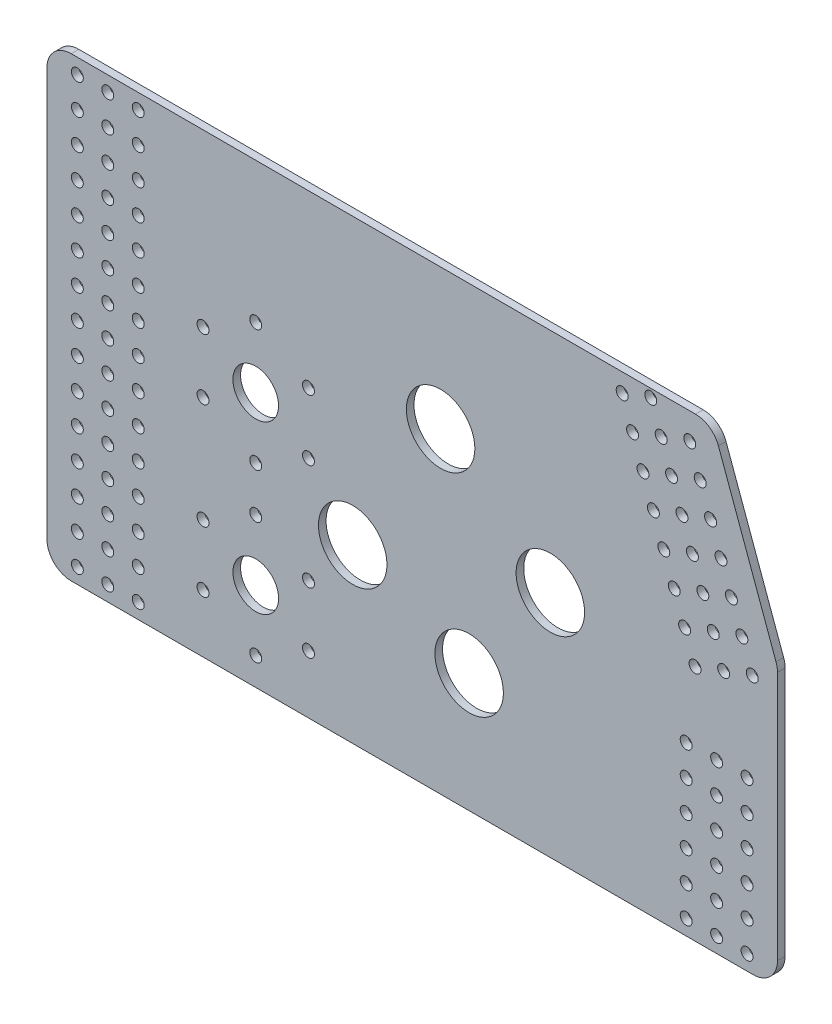
SolidWorks part; units mm, degrees
ref_plane "Front Plane" through (0, 0, 0) normal (0, 0, 1) x (1, 0, 0)
ref_plane "Top Plane" through (0, 0, 0) normal (0, 1, 0) x (1, 0, 0)
ref_plane "Right Plane" through (0, 0, 0) normal (1, 0, 0) x (0, 0, -1)
sketch "Sketch1" plane through (0, 0, 0) normal (0, 0, 1) x (1, 0, 0)
  line B0 (-152.4, 0) -> (152.4, 0)
  line B1 (152.4, 0) -> (152.4, 116.0843)
  line B2 (152.4, 116.0843) -> (125.3149, 190.5)
  line B3 (125.3149, 190.5) -> (-152.4, 190.5)
  line B4 (-152.4, 190.5) -> (-152.4, 0)
  circle B5 centre (-139.7, 184.15) radius 2.4892
  circle B6 centre (-127, 184.15) radius 2.4892
  circle B7 centre (-114.3, 184.15) radius 2.4892
  circle B8 centre (-127, 171.45) radius 2.4892
  circle B9 centre (-114.3, 171.45) radius 2.4892
  circle B10 centre (-127, 158.75) radius 2.4892
  circle B11 centre (-114.3, 158.75) radius 2.4892
  circle B12 centre (-127, 146.05) radius 2.4892
  circle B13 centre (-114.3, 146.05) radius 2.4892
  circle B14 centre (-127, 133.35) radius 2.4892
  circle B15 centre (-114.3, 133.35) radius 2.4892
  circle B16 centre (-127, 120.65) radius 2.4892
  circle B17 centre (-114.3, 120.65) radius 2.4892
  circle B18 centre (-127, 107.95) radius 2.4892
  circle B19 centre (-114.3, 107.95) radius 2.4892
  circle B20 centre (-127, 95.25) radius 2.4892
  circle B21 centre (-114.3, 95.25) radius 2.4892
  circle B22 centre (-127, 82.55) radius 2.4892
  circle B23 centre (-114.3, 82.55) radius 2.4892
  circle B24 centre (-127, 69.85) radius 2.4892
  circle B25 centre (-114.3, 69.85) radius 2.4892
  circle B26 centre (-127, 57.15) radius 2.4892
  circle B27 centre (-114.3, 57.15) radius 2.4892
  circle B28 centre (-127, 44.45) radius 2.4892
  circle B29 centre (-114.3, 44.45) radius 2.4892
  circle B30 centre (-127, 31.75) radius 2.4892
  circle B31 centre (-114.3, 31.75) radius 2.4892
  circle B32 centre (-127, 19.05) radius 2.4892
  circle B33 centre (-114.3, 19.05) radius 2.4892
  circle B34 centre (-127, 6.35) radius 2.4892
  circle B35 centre (-114.3, 6.35) radius 2.4892
  circle B36 centre (-139.7, 171.45) radius 2.4892
  circle B37 centre (-139.7, 158.75) radius 2.4892
  circle B38 centre (-139.7, 146.05) radius 2.4892
  circle B39 centre (-139.7, 133.35) radius 2.4892
  circle B40 centre (-139.7, 120.65) radius 2.4892
  circle B41 centre (-139.7, 107.95) radius 2.4892
  circle B42 centre (-139.7, 95.25) radius 2.4892
  circle B43 centre (-139.7, 82.55) radius 2.4892
  circle B44 centre (-139.7, 69.85) radius 2.4892
  circle B45 centre (-139.7, 57.15) radius 2.4892
  circle B46 centre (-139.7, 44.45) radius 2.4892
  circle B47 centre (-139.7, 31.75) radius 2.4892
  circle B48 centre (-139.7, 19.05) radius 2.4892
  circle B49 centre (-139.7, 6.35) radius 2.4892
  circle B50 centre (87.5907, 182.7494) radius 2.4892
  circle B51 centre (99.5248, 187.093) radius 2.4892
  circle B52 centre (115.8026, 179.5026) radius 2.4892
  circle B53 centre (91.9344, 170.8153) radius 2.4892
  circle B54 centre (103.8685, 175.1589) radius 2.4892
  circle B55 centre (120.1462, 167.5685) radius 2.4892
  circle B56 centre (96.278, 158.8812) radius 2.4892
  circle B57 centre (108.2121, 163.2248) radius 2.4892
  circle B58 centre (124.4899, 155.6344) radius 2.4892
  circle B59 centre (100.6217, 146.9471) radius 2.4892
  circle B60 centre (112.5558, 151.2907) radius 2.4892
  circle B61 centre (128.8335, 143.7003) radius 2.4892
  circle B62 centre (104.9653, 135.013) radius 2.4892
  circle B63 centre (116.8994, 139.3566) radius 2.4892
  circle B64 centre (133.1772, 131.7662) radius 2.4892
  circle B65 centre (109.309, 123.0789) radius 2.4892
  circle B66 centre (121.2431, 127.4226) radius 2.4892
  circle B67 centre (137.5208, 119.8321) radius 2.4892
  circle B68 centre (113.6526, 111.1448) radius 2.4892
  circle B69 centre (125.5867, 115.4885) radius 2.4892
  circle B70 centre (141.8645, 107.898) radius 2.4892
  circle B71 centre (117.9963, 99.2107) radius 2.4892
  circle B72 centre (129.9304, 103.5544) radius 2.4892
  circle B73 centre (146.2081, 95.9639) radius 2.4892
  circle B74 centre (114.3, 69.85) radius 2.4892
  circle B75 centre (127, 69.85) radius 2.4892
  circle B76 centre (139.7, 69.85) radius 2.4892
  circle B77 centre (114.3, 57.15) radius 2.4892
  circle B78 centre (127, 57.15) radius 2.4892
  circle B79 centre (139.7, 57.15) radius 2.4892
  circle B80 centre (114.3, 44.45) radius 2.4892
  circle B81 centre (127, 44.45) radius 2.4892
  circle B82 centre (139.7, 44.45) radius 2.4892
  circle B83 centre (114.3, 31.75) radius 2.4892
  circle B84 centre (127, 31.75) radius 2.4892
  circle B85 centre (139.7, 31.75) radius 2.4892
  circle B86 centre (114.3, 19.05) radius 2.4892
  circle B87 centre (127, 19.05) radius 2.4892
  circle B88 centre (139.7, 19.05) radius 2.4892
  circle B89 centre (114.3, 6.35) radius 2.4892
  circle B90 centre (127, 6.35) radius 2.4892
  circle B91 centre (139.7, 6.35) radius 2.4892
  circle B92 centre (11.8508, 132.0168) radius 14.2875
  circle B93 centre (-24.8197, 71.7449) radius 14.2875
  circle B94 centre (57.6351, 95.7125) radius 14.2875
  circle B95 centre (23.7546, 49.6787) radius 14.2875
  circle B96 centre (-65.2702, 36.9534) radius 9.525
  circle B97 centre (-65.2702, 106.5494) radius 9.525
  circle B98 centre (-65.2702, 131.9494) radius 2.4892
  circle B99 centre (-65.2702, 11.5534) radius 2.4892
  circle B100 centre (-43.2731, 119.2494) radius 2.4892
  circle B101 centre (-43.2731, 93.8494) radius 2.4892
  circle B102 centre (-65.2702, 81.1494) radius 2.4892
  circle B103 centre (-87.2672, 93.8494) radius 2.4892
  circle B104 centre (-87.2672, 119.2494) radius 2.4892
  circle B105 centre (-87.2672, 24.2534) radius 2.4892
  circle B106 centre (-87.2672, 49.6534) radius 2.4892
  circle B107 centre (-65.2702, 62.3534) radius 2.4892
  circle B108 centre (-43.2731, 49.6534) radius 2.4892
  circle B109 centre (-43.2731, 24.2534) radius 2.4892
sketch_block_instance "Block-InnerPlate-1"
sketch_block "Block-InnerPlate" parameters "D1"=4.9784, "D7"=4.9784, "D8"=4.9784, "D9"=4.9784, "D11"=4.9784, "D12"=4.9784, "D13"=4.9784, "D15"=19.05, "D16"=19.05, "D17"=28.575, "D18"=28.575, "D19"=28.575, "D20"=28.575, "D21"=4.9784, "D22"=4.9784, "D2"=6.35, "D3"=12.7, "D4"=12.7, "D5"=12.7, "D6"=6.35, "D10"=12.7, "D14"=12.7, "D23"=25.4, "D24"=25.4
extrude "Boss-Extrude1" add sketch "Sketch1" along normal blind 3.175
sketch "Sketch2" plane through (0, 0, 3.175) normal (0, 0, 1) x (1, 0, 0)
  circle A0 centre (146.2081, 95.9639) radius 2.4892
  dimension "D1" = 4.9784
extrude "Boss-Extrude2" add sketch "Sketch2" against normal blind 3.175
fillet "Fillet1" radius 10.16 5 edges at (-152.4, 0, 1.5875) (152.4, 0, 1.5875) (152.4, 116.0843, 1.5875) (125.3149, 190.5, 1.5875) (-152.4, 190.5, 1.5875)
